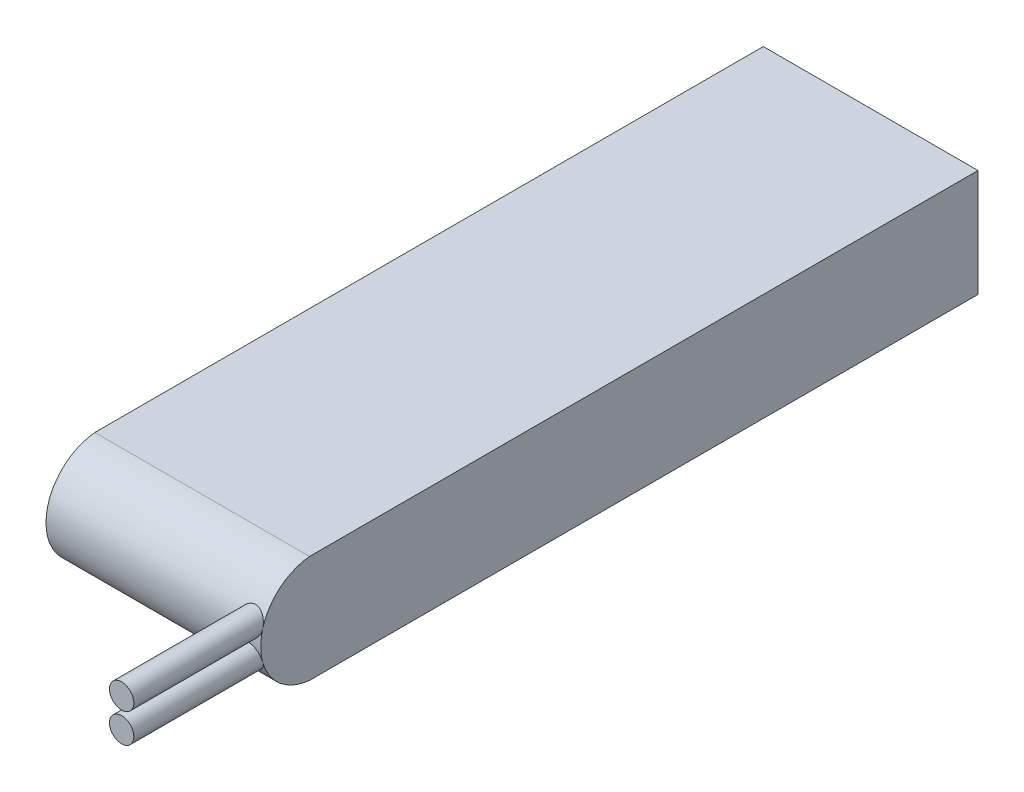
SolidWorks part; units mm, degrees
ref_plane "Plan de face" through (0, 0, 0) normal (0, 0, 1) x (1, 0, 0)
ref_plane "Plan de dessus" through (0, 0, 0) normal (0, 1, 0) x (1, 0, 0)
ref_plane "Plan de droite" through (0, 0, 0) normal (1, 0, 0) x (0, 0, -1)
sketch "Esquisse1" plane through (0, 0, 0) normal (0, 0, 1) x (1, 0, 0)
  line L1 (0, 0) -> (44, 0)
  line L2 (0, 0) -> (0, 22)
  line L3 (0, 22) -> (44, 22)
  line L4 (44, 0) -> (44, 22)
  dimension "D1" = 22
  dimension "D2" = 44
extrude "Boss.-Extru.1" add sketch "Esquisse1" along normal blind 137
sketch "Esquisse2" plane through (44, 0, 0) normal (1, 0, 0) x (0, 0, -1)
  line L0 (-137, 0) -> (-137, 22) construction
  line L1 (-137, 22) -> (-137, 0)
  arc A0 (-137, 22) -> (-137, 0) centre (-135.95, 11) ccw
  point P7 (-147, 11)
  dimension "D1" = 10
extrude "Boss.-Extru.2" add sketch "Esquisse2" against normal up to vertex (44 mm away) up to point (0, 22, 137)
sketch "Esquisse3" plane through (0, 0, 0) normal (0, 0, -1) x (-1, 0, 0)
  line L0 (-44, 0) -> (-44, 22) construction
  line L1 (-41.5, 14) -> (-41.5, 8) construction
  line L2 (-44, 11) -> (0, 11) construction
  line L3 (0, 22) -> (0, 0) construction
  circle A0 centre (-41.5, 14) radius 2.5
  circle A1 centre (-41.5, 8) radius 2.5
  point P9 (-41.5, 8)
  dimension "D1" = 5
  dimension "D2" = 3
  dimension "D3" = 3
extrude "Boss.-Extru.3" add sketch "Esquisse3" against normal blind 173
